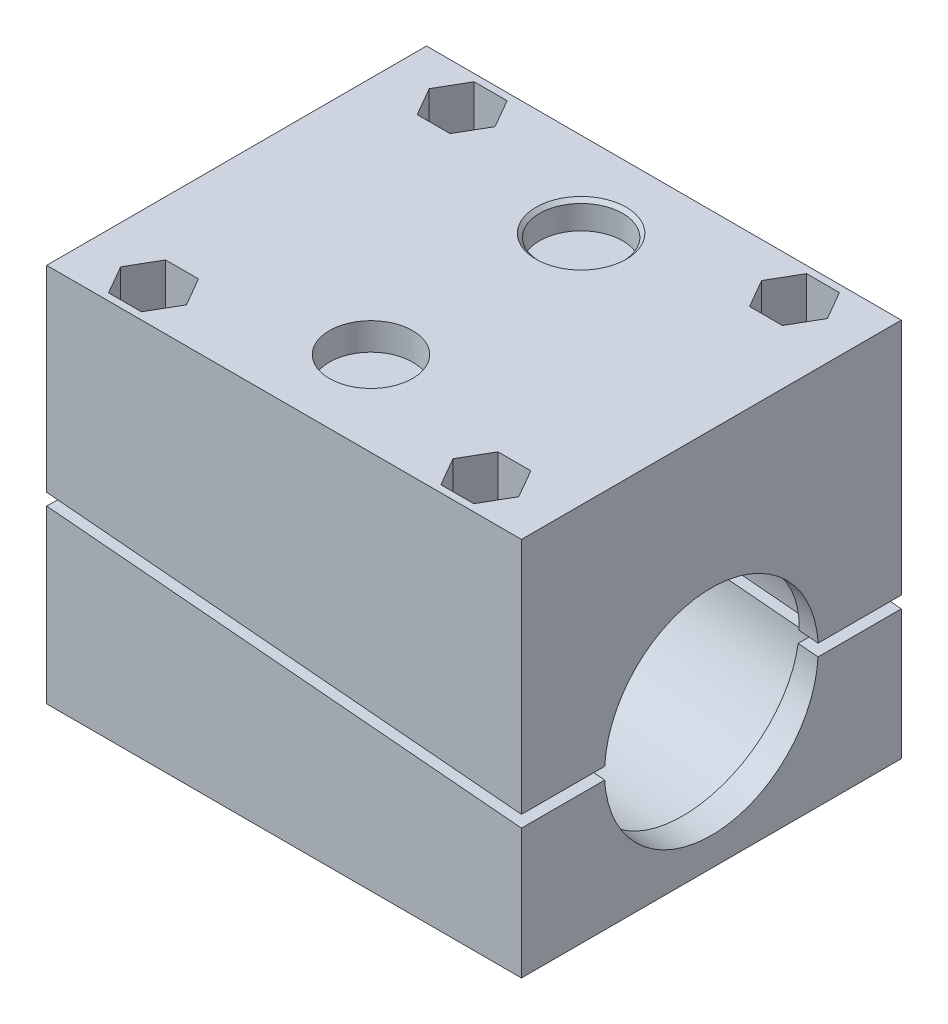
SolidWorks part; units mm, degrees
other "Markup1"
sketch "Sketch6" plane through (-20, 35, 16) normal (-0.9068, 0.0323, 0.4203) x (0.4191, -0.0374, 0.9072)
ref_plane "Front Plane" through (0, 0, 0) normal (0, 0, 1) x (1, 0, 0)
ref_plane "Top Plane" through (0, 0, 0) normal (0, 1, 0) x (1, 0, 0)
ref_plane "Right Plane" through (0, 0, 0) normal (1, 0, 0) x (0, 0, -1)
sketch "Sketch1" plane through (0, 0, 0) normal (0, 1, 0) x (1, 0, 0)
  line L0 (-77.0138, 0) -> (0, 0) construction
  line L1 (-20, -16) -> (20, -16)
  line L2 (-20, -16) -> (-20, 16)
  line L3 (-20, 16) -> (20, 16)
  line L4 (20, -16) -> (20, 16)
  line L5 (-20, -16) -> (20, 16) construction
  line L6 (-20, 16) -> (20, -16) construction
  line L7 (-213.5568, -10) -> (59.5292, -10) construction
  line L8 (-213.5568, -10) -> (-213.5568, 10) construction
  line L9 (-213.5568, 10) -> (59.5292, 10) construction
  line L10 (59.5292, -10) -> (59.5292, 10) construction
  line L11 (-213.5568, -10) -> (59.5292, 10) construction
  line L12 (-213.5568, 10) -> (59.5292, -10) construction
  point P0 (0, 0)
  point P6 (-77.0138, 0)
  dimension "D1" = 20
  dimension "D2" = 32
  dimension "D3" = 40
extrude "Boss-Extrude1" add sketch "Sketch1" along normal blind 32
ref_plane "Plane1" through (-22.6264, 1.9796, 0) normal (-0.9962, 0.0872, 0) x (0, 0, 1)
sketch "Sketch2" plane through (-22.6264, 1.9796, 0) normal (-0.9962, 0.0872, 0) x (0, 0, 1)
  line L0 (0, 30.1351) -> (0, -1.7431) construction
  line L1 (-16, 30.1351) -> (16, 30.1351) construction
  line L2 (-16, -1.7431) -> (16, -1.7431) construction
  circle A0 centre (0, 13.1351) radius 10.1
  dimension "D2" = 20.2
  dimension "D1" = 17
extrude "Cut-Extrude1" cut sketch "Sketch2" against normal blind 40
sketch "Sketch3" plane through (0, 0, 0) normal (0, 1, 0) x (1, 0, 0)
  line L0 (20, 13) -> (-20, 13) construction
  line L1 (20, -16) -> (20, 16) construction
  line L2 (-20, -16) -> (-20, 16) construction
  line L3 (-20, 16) -> (20, 16) construction
  line L4 (20, 0) -> (-20, 0) construction
  circle A0 centre (-14, 13) radius 1.75
  circle A1 centre (14, 13) radius 1.75
  circle A2 centre (14, -13) radius 1.75
  circle A3 centre (-14, -13) radius 1.75
  dimension "D1" = 3.5
  dimension "D2" = 3
  dimension "D3" = 6
  dimension "D4" = 6
extrude "Cut-Extrude2" cut sketch "Sketch3" along normal through all
sketch "Sketch4" plane through (0, 0, 0) normal (0, 0, 1) x (1, 0, 0)
  line L0 (-21.4816, 15.0647) -> (31.8697, 10.397) construction
  line L1 (-20, 32) -> (-22.7784, 0.2431) construction
  line L2 (31.8262, 9.899) -> (31.9133, 10.8951)
  line L3 (31.9133, 10.8951) -> (-21.4381, 15.5628)
  line L4 (31.8262, 9.899) -> (-21.5252, 14.5666)
  line L5 (-21.5252, 14.5666) -> (-21.4381, 15.5628)
  point P8 (31.8697, 10.397)
  dimension "D1" = 1
sketch "Sketch5" plane through (0, 0, 0) normal (0, 1, 0) x (1, 0, 0)
  line L0 (20, -16) -> (20, 16) construction
  line L1 (8, -19.589) -> (-8, -19.589)
  line L2 (8, -19.589) -> (8, 19.589)
  line L3 (8, 19.589) -> (-8, 19.589)
  line L4 (-8, -19.589) -> (-8, 19.589)
  line L5 (8, -19.589) -> (-8, 19.589) construction
  line L6 (8, 19.589) -> (-8, -19.589) construction
  point P0 (0, 0)
  dimension "D1" = 12
ref_plane "Plane2" through (0, 32, 0) normal (0, 1, 0) x (1, 0, 0)
sketch "Sketch7" plane through (0, 32, 0) normal (0, 1, 0) x (1, 0, 0)
  line L1 (-11.2287, 13) -> (-12.6144, 15.4)
  line L2 (-12.6144, 15.4) -> (-15.3856, 15.4)
  line L3 (-15.3856, 15.4) -> (-16.7713, 13)
  line L4 (-16.7713, 13) -> (-15.3856, 10.6)
  line L5 (-15.3856, 10.6) -> (-12.6144, 10.6)
  line L6 (-12.6144, 10.6) -> (-11.2287, 13)
  line L7 (16.7713, 13) -> (15.3856, 15.4)
  line L8 (15.3856, 15.4) -> (12.6144, 15.4)
  line L9 (12.6144, 15.4) -> (11.2287, 13)
  line L10 (11.2287, 13) -> (12.6144, 10.6)
  line L11 (12.6144, 10.6) -> (15.3856, 10.6)
  line L12 (15.3856, 10.6) -> (16.7713, 13)
  line L13 (16.7713, -13) -> (15.3856, -10.6)
  line L14 (15.3856, -10.6) -> (12.6144, -10.6)
  line L15 (12.6144, -10.6) -> (11.2287, -13)
  line L16 (11.2287, -13) -> (12.6144, -15.4)
  line L17 (12.6144, -15.4) -> (15.3856, -15.4)
  line L18 (15.3856, -15.4) -> (16.7713, -13)
  line L19 (-11.2287, -13) -> (-12.6144, -10.6)
  line L20 (-12.6144, -10.6) -> (-15.3856, -10.6)
  line L21 (-15.3856, -10.6) -> (-16.7713, -13)
  line L22 (-16.7713, -13) -> (-15.3856, -15.4)
  line L23 (-15.3856, -15.4) -> (-12.6144, -15.4)
  line L24 (-12.6144, -15.4) -> (-11.2287, -13)
  circle A0 centre (-14, 13) radius 2.4 construction
  circle A1 centre (14, 13) radius 2.4 construction
  circle A2 centre (14, -13) radius 2.4 construction
  circle A3 centre (-14, -13) radius 2.4 construction
  dimension "D1" = 4.8
extrude "Cut-Extrude3" cut sketch "Sketch7" against normal blind 13
split "Split2" trim tools "Sketch4" bodies to split 137 resulting bodies 141 142
sketch "Sketch10" plane through (0, 0, 0) normal (0, 1, 0) x (1, 0, 0)
  circle A0 centre (0.1726, -8.8514) radius 3.5
  circle A1 centre (0.1726, 8.8514) radius 3.5
  dimension "D1" = 7
  dimension "D2" = 7
extrude "Cut-Extrude5" cut sketch "Sketch10" along normal blind 2.3
sketch "Sketch11" plane through (0, 32, 0) normal (0, 1, 0) x (1, 0, 0)
  circle A0 centre (0.1726, -8.8514) radius 3.5
  circle A1 centre (0.1726, 8.8514) radius 3.5
  dimension "D1" = 7
  dimension "D2" = 7
extrude "Cut-Extrude6" cut sketch "Sketch11" against normal blind 2.3
sketch "Sketch12" plane through (-22.6264, 1.9796, 0) normal (-0.9962, 0.0872, 0) x (0, 0, 1)
  circle A0 centre (0, 13.1351) radius 9
  dimension "D1" = 18
extrude "Cut-Extrude7" cut sketch "Sketch12" against normal through all
chamfer "Chamfer3" distance 0.3 angle 45 1 edges at (0.1726, 32, -5.3514)
chamfer "Chamfer4" distance 0.3 angle 45 1 edges at (0.1726, 0, -5.3514)
